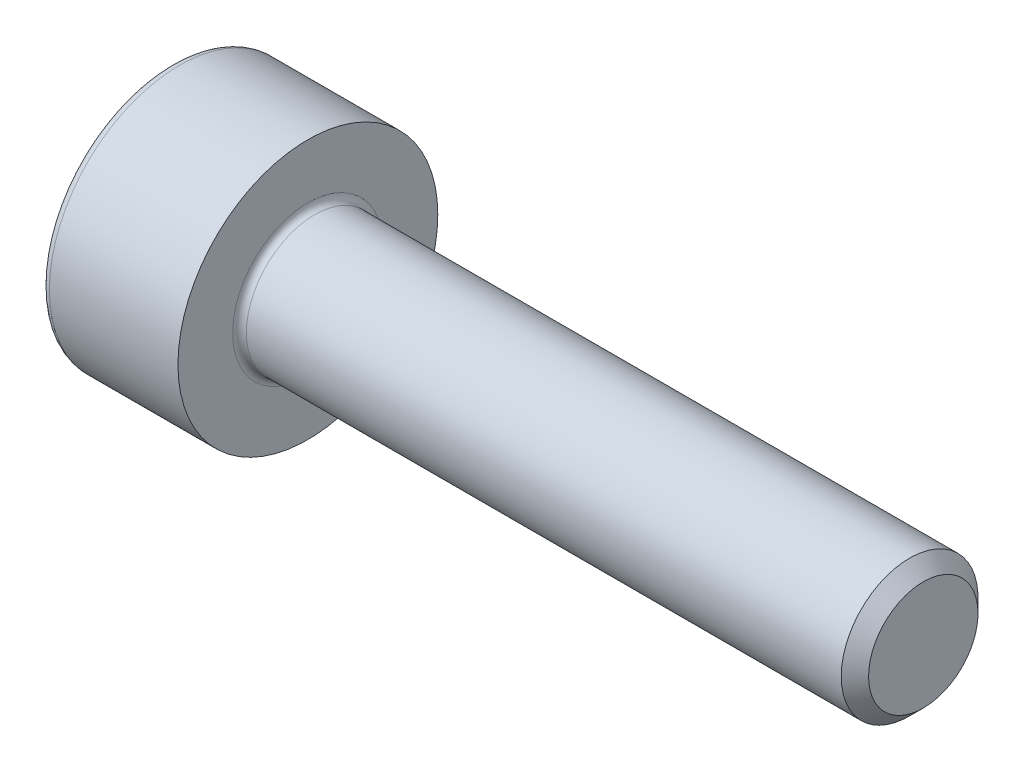
SolidWorks part; units mm, degrees
ref_plane "Front Plane" through (0, 0, 0) normal (0, 0, 1) x (1, 0, 0)
ref_plane "Top Plane" through (0, 0, 0) normal (0, 1, 0) x (1, 0, 0)
ref_plane "Right Plane" through (0, 0, 0) normal (1, 0, 0) x (0, 0, -1)
sketch "Sketch1" plane through (0, 0, 0) normal (0, 0, 1) x (1, 0, 0)
  line L0 (0, 0) -> (0, 1.9)
  line L1 (0, 1.9) -> (2, 1.9)
  line L2 (2, 1.9) -> (2, 0)
  line L3 (0, 0) -> (4.2799, 0) construction
  line L4 (2, 0) -> (11, 0)
  line L5 (11, 0) -> (11, 1)
  line L6 (11, 1) -> (2, 1)
  dimension "D1" = 9
revolve "Revolve1" add sketch "Sketch1" angle 360 about L3
fillet "Fillet1" radius 0.1 1 edges at (2, 0, 1)
fillet "Fillet2" radius 0.12 1 edges at (0, 0, 1.9)
chamfer "Chamfer1" distance 0.2 angle 45 1 edges at (11, 0, 1)
sketch "Sketch2" plane through (0, 0, 0) normal (-1, 0, 0) x (0, 0, 1)
  line L1 (0, 0.866) -> (-0.75, 0.433)
  line L2 (-0.75, 0.433) -> (-0.75, -0.433)
  line L3 (-0.75, -0.433) -> (0, -0.866)
  line L4 (0, -0.866) -> (0.75, -0.433)
  line L5 (0.75, -0.433) -> (0.75, 0.433)
  line L6 (0.75, 0.433) -> (0, 0.866)
  circle A0 centre (0, 0) radius 0.75 construction
extrude "Extrude1" cut sketch "Sketch2" against normal blind 1
